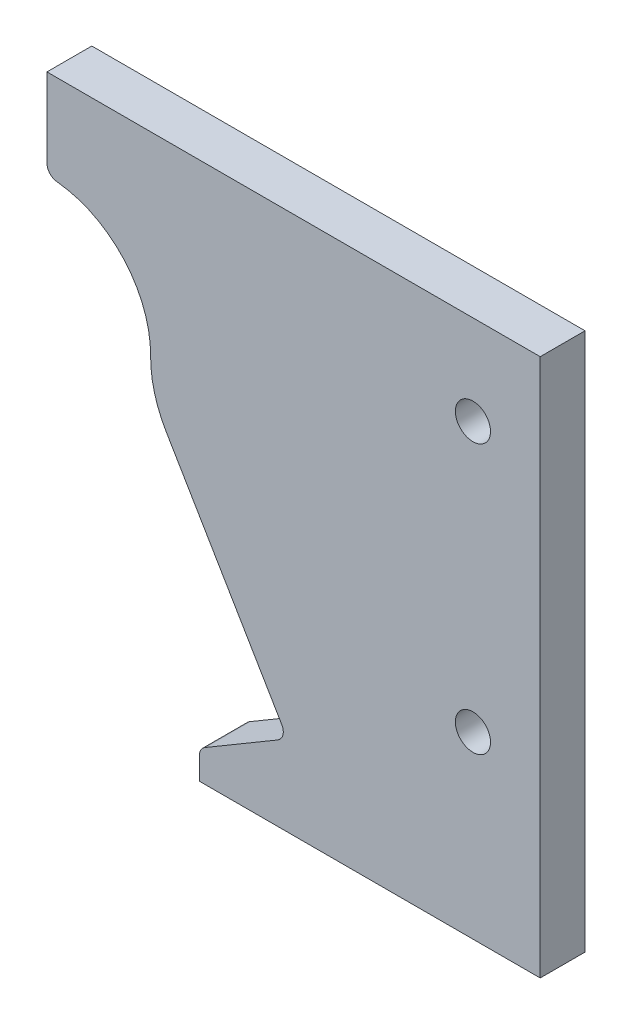
SolidWorks part; units mm, degrees
material "6061 Alloy"
ref_plane "X-Y Datum" through (0, 0, 0) normal (0, 0, 1) x (1, 0, 0)
ref_plane "X-Z Datum" through (0, 0, 0) normal (0, 1, 0) x (1, 0, 0)
ref_plane "Y-Z Datum" through (0, 0, 0) normal (1, 0, 0) x (0, 0, -1)
sketch "Sketch1" plane through (0, 0, 0) normal (0, 0, 1) x (1, 0, 0)
  line L0 (69.85, 27.3812) -> (69.85, -48.8188)
  line L3 (69.85, -48.8188) -> (21.5766, -48.8188)
  line L8 (21.5766, -44.7629) -> (34.055, -37.3978)
  line L9 (34.055, -37.3978) -> (16.884, -8.3053)
  line L11 (21.5766, -48.8188) -> (21.5766, -44.7629)
  line L26 (0, 14.6812) -> (0, 27.3812)
  line L27 (0, 0) -> (0, 14.6812) construction
  line L28 (0, 27.3812) -> (69.85, 27.3812)
  arc A5 (14.6808, -0.1135) -> (0, 14.6812) centre (0, 0) ccw
  arc A6 (16.884, -8.3053) -> (14.6808, -0.1135) centre (30.5553, -0.2362) cw
  circle A8 centre (60.325, 14.6812) radius 2.4892
  circle A9 centre (60.325, -23.4188) radius 2.4892
  dimension "D4" = 15.875
  dimension "D8" = 14.6812
  dimension "D7" = 4.9784
  dimension "D2" = 21.5766
  dimension "D3" = 14.6808
  dimension "D5" = 34.055
  dimension "D6" = 16.884
  dimension "D9" = 76.2
  dimension "D10" = 12.7
  dimension "D11" = 69.85
  dimension "D12" = 12.7
  dimension "D13" = 25.4
  dimension "D14" = 9.525
  dimension "D15" = 9.525
extrude "Boss-Extrude1" add sketch "Sketch1" along normal mid plane 6.35
fillet "Fillet1" radius 1.5875 3 edges at (0, 14.6812, 0) (21.5766, -44.7629, 0) (34.055, -37.3978, 0)
